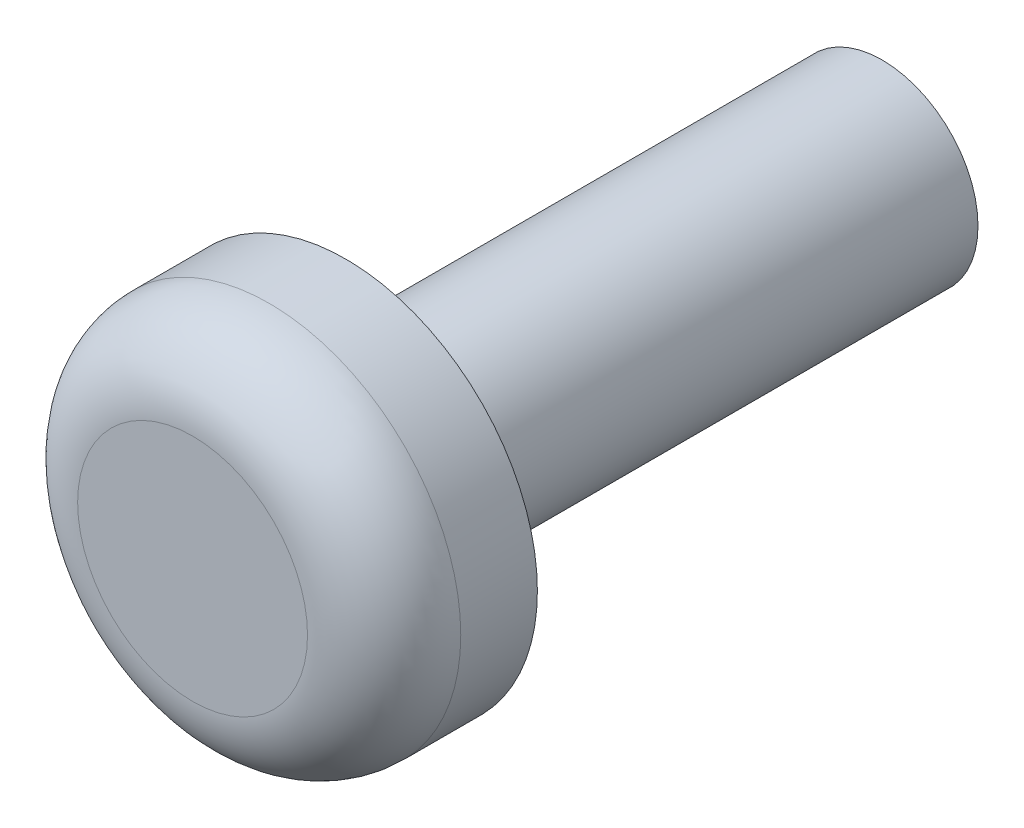
SolidWorks part; units mm, degrees
material "AISI 1045 Steel, cold drawn"
ref_plane "Front Plane" through (0, 0, 0) normal (0, 0, 1) x (1, 0, 0)
ref_plane "Top Plane" through (0, 0, 0) normal (0, 1, 0) x (1, 0, 0)
ref_plane "Right Plane" through (0, 0, 0) normal (1, 0, 0) x (0, 0, -1)
sketch "Sketch1" plane through (0, 0, 0) normal (0, 0, 1) x (1, 0, 0)
  circle A0 centre (0, 0) radius 1.25
  dimension "D1" = 2.5
extrude "Boss-Extrude1" add sketch "Sketch1" along normal blind 7
sketch "Sketch2" plane through (0, 0, 7) normal (0, 0, 1) x (1, 0, 0)
  circle A0 centre (0, 0) radius 2.5
extrude "Boss-Extrude2" add sketch "Sketch2" along normal blind 2
fillet "Fillet1" radius 1 1 edges at (2.5, 0, 9)
